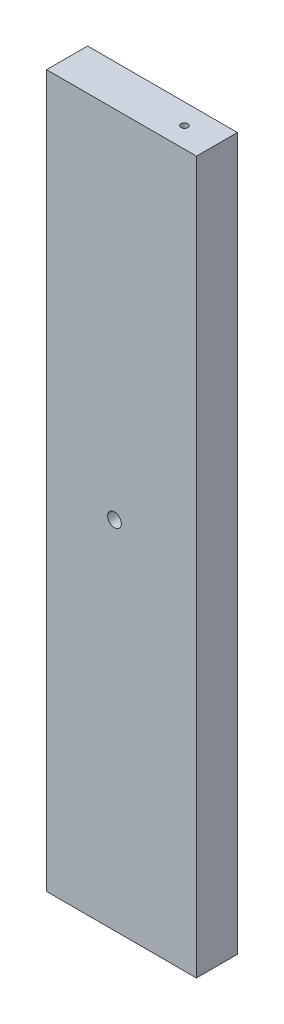
SolidWorks part; units mm, degrees
material "Beech"
ref_plane "Front Plane" through (0, 0, 0) normal (0, 0, 1) x (1, 0, 0)
ref_plane "Top Plane" through (0, 0, 0) normal (0, 1, 0) x (1, 0, 0)
ref_plane "Right Plane" through (0, 0, 0) normal (1, 0, 0) x (0, 0, -1)
sketch "Sketch1" plane through (0, 0, 0) normal (0, 0, 1) x (1, 0, 0)
  line L1 (209.353, 93.45) -> (279.0199, 93.45)
  line L2 (209.353, 93.45) -> (209.353, -237.5)
  line L3 (209.353, -237.5) -> (279.0199, -237.5)
  line L4 (279.0199, 93.45) -> (279.0199, -237.5)
  point P4 (279.0199, -237.5)
  dimension "D1" = 69.667
extrude "Boss-Extrude1" add sketch "Sketch1" along normal blind 19.05
hole_wizard "Hole1" [suppressed] positions "Sketch2" profile "Sketch3" legacy
sketch "Sketch2" [suppressed] plane through (196.653, -72.025, 386.2628) normal (-1, 0, 0) x (0, 1, 0)
  point P49 (175, 685.961)
  point P51 (175, 549.8373)
  point P53 (175, 413.7135)
  point P67 (81.55, 779.6497)
  point P73 (81.55, 652.3446)
  point P79 (62.5, 662.9534)
  point P83 (62.5, 769.041)
  point P103 (-62.5, 769.041)
  point P105 (-62.5, 662.9534)
  point P106 (-81.55, 652.3446)
  point P109 (-81.55, 779.6497)
  point P110 (-175, 413.7135)
  point P111 (-175, 549.8373)
  point P112 (-175, 685.961)
  point P115 (-82.7375, 600.3846)
  point P117 (0, 600.3846)
  point P119 (82.7375, 600.3846)
  point P129 (0, 376.7378)
  point P131 (-82.7375, 376.7378)
  point P133 (82.7375, 376.7378)
sketch "Sketch3" plane through (196.653, 102.975, -299.6982) normal (0, 1, 0) x (0, 0, 1)
  line L0 (0, 0) -> (0, 32.7039)
  line L1 (0, 32.7039) -> (1.5875, 31.75)
  line L2 (1.5875, 31.75) -> (1.5875, 4.0177)
  line L3 (1.5875, 4.0177) -> (5.08, 0)
  line L4 (5.08, 0) -> (0, 0)
  line L5 (0, -14.3089) -> (0, 102.4216) construction
  line L6 (0, 32.7039) -> (-1.5875, 31.75) construction
  line L7 (-1.5875, 4.0177) -> (-5.08, 0) construction
  dimension "Diameter" = 3.175
  dimension "Depth" = 31.75
  dimension "C-Sink Diameter" = 10.16
  dimension "C-Sink Angle" = 82
  dimension "Drill Angle" = 118
hole_wizard "Hole3" positions "Sketch6" profile "Sketch7" legacy
sketch "Sketch6" plane through (-181.0394, 112.5, 410.3892) normal (0, 1, 0) x (0.9272, 0, -0.3746)
  line L0 (48.5061, 138.7859) -> (35.9701, 0) construction
  line L5 (414.5728, 105.7206) -> (405.0235, 0) construction
  line L7 (490.0108, 170.6797) -> (621.0107, 117.7523) construction
  line L12 (503.094, 203.0616) -> (634.0938, 150.1342) construction
  line L16 (586.8736, 410.4234) -> (717.8734, 357.496) construction
  line L19 (597.4602, 127.2674) -> (610.5433, 159.6493) construction
  line L20 (610.5433, 159.6493) -> (694.3229, 367.011) construction
  line L22 (513.5613, 161.1647) -> (526.6445, 193.5466) construction
  line L23 (526.6445, 193.5466) -> (610.424, 400.9084) construction
  point P0 (46.2211, 113.4889)
  point P2 (39.3976, 37.9455)
  point P4 (412.2879, 80.4236)
  point P51 (407.3085, 25.297)
  point P56 (513.5613, 161.1647)
  point P58 (597.4602, 127.2674)
  point P61 (610.5433, 159.6493)
  point P63 (694.3229, 367.011)
  point P66 (526.6445, 193.5466)
  point P68 (610.424, 400.9084)
sketch "Sketch7" plane through (-180.6976, 112.5, 287.8494) normal (1, 0, 0) x (0, 0, 1)
  line L0 (0, 0) -> (0, 39.0539)
  line L1 (0, 39.0539) -> (1.5875, 38.1)
  line L2 (1.5875, 38.1) -> (1.5875, 4.0177)
  line L3 (1.5875, 4.0177) -> (5.08, 0)
  line L4 (5.08, 0) -> (0, 0)
  line L5 (0, -14.3089) -> (0, 102.4216) construction
  line L6 (0, 39.0539) -> (-1.5875, 38.1) construction
  line L7 (-1.5875, 4.0177) -> (-5.08, 0) construction
  dimension "Diameter" = 3.175
  dimension "Depth" = 38.1
  dimension "C-Sink Diameter" = 10.16
  dimension "C-Sink Angle" = 82
  dimension "Drill Angle" = 118
hole_wizard "1/4 (0.25) Diameter Hole1" positions "Sketch10" profile "Sketch11" hole size "1/4" standard "ANSI Inch" end condition through all
sketch "Sketch10" plane through (0, 0, 0) normal (0, 0, -1) x (-1, 0, 0)
  point P0 (-240.9199, -72.025)
  point P1 (0, 0)
  point P2 (-240.9199, -72.025)
sketch "Sketch11" plane through (240.9199, -72.025, 0) normal (1, 0, 0) x (0, 1, 0)
  line L0 (0, 0) -> (0, 19.05)
  line L1 (0, 19.05) -> (3.175, 19.05)
  line L2 (3.175, 19.05) -> (3.175, 0)
  line L5 (3.175, 0) -> (0, 0)
  line L11 (0, -6.35) -> (0, 107.95) construction
  dimension "Thru Hole Dia." = 6.35
  dimension "Thru Hole Depth" = 19.05
hole_wizard "Hole4" [suppressed] positions "Sketch12" profile "Sketch13" legacy
sketch "Sketch12" [suppressed] plane through (196.653, -72.025, 609.9096) normal (-1, 0, 0) x (0, 1, 0)
  point P49 (175, 685.961)
  point P51 (175, 549.8373)
  point P53 (175, 413.7135)
  point P67 (81.55, 779.6497)
  point P73 (81.55, 652.3446)
  point P79 (62.5, 662.9534)
  point P83 (62.5, 769.041)
  point P103 (-62.5, 769.041)
  point P105 (-62.5, 662.9534)
  point P106 (-81.55, 652.3446)
  point P109 (-81.55, 779.6497)
  point P110 (-175, 413.7135)
  point P111 (-175, 549.8373)
  point P112 (-175, 685.961)
  point P115 (-82.7375, 600.3846)
  point P117 (0, 600.3846)
  point P119 (82.7375, 600.3846)
  point P129 (0, 376.7378)
  point P131 (-82.7375, 376.7378)
  point P133 (82.7375, 376.7378)
sketch "Sketch13" plane through (196.653, 102.975, -76.0514) normal (0, 1, 0) x (0, 0, 1)
  line L0 (0, 0) -> (0, 32.7039)
  line L1 (0, 32.7039) -> (1.5875, 31.75)
  line L2 (1.5875, 31.75) -> (1.5875, 4.0177)
  line L3 (1.5875, 4.0177) -> (5.08, 0)
  line L4 (5.08, 0) -> (0, 0)
  line L5 (0, -14.3089) -> (0, 102.4216) construction
  line L6 (0, 32.7039) -> (-1.5875, 31.75) construction
  line L7 (-1.5875, 4.0177) -> (-5.08, 0) construction
  dimension "Diameter" = 3.175
  dimension "Depth" = 31.75
  dimension "C-Sink Diameter" = 10.16
  dimension "C-Sink Angle" = 82
  dimension "Drill Angle" = 118
hole_wizard "Hole5" positions "Sketch14" profile "Sketch15" legacy
sketch "Sketch14" plane through (-181.0394, 112.5, 580.9729) normal (0, 1, 0) x (0.9272, 0, -0.3746)
  line L0 (79.9741, 138.7859) -> (67.4382, 0) construction
  line L5 (446.0409, 105.7206) -> (436.4916, 0) construction
  line L7 (526.1009, 182.1196) -> (590.695, 156.0219) construction
  line L12 (512.1319, 225.4312) -> (576.726, 199.3335) construction
  line L16 (576.0337, 383.5937) -> (640.6278, 357.496) construction
  line L19 (567.1445, 165.5369) -> (580.2277, 197.9188) construction
  line L20 (580.2277, 197.9188) -> (644.1295, 356.0812) construction
  line L22 (549.6514, 172.6046) -> (562.7345, 204.9865) construction
  line L23 (562.7345, 204.9865) -> (626.6363, 363.1489) construction
  point P0 (77.6892, 113.4889)
  point P2 (70.8657, 37.9455)
  point P4 (443.7559, 80.4236)
  point P51 (438.7766, 25.297)
  point P56 (549.6514, 172.6046)
  point P58 (567.1445, 165.5369)
  point P61 (580.2277, 197.9188)
  point P63 (644.1295, 356.0812)
  point P66 (562.7345, 204.9865)
  point P68 (626.6363, 363.1489)
sketch "Sketch15" plane through (-151.521, 112.5, 446.645) normal (1, 0, 0) x (0, 0, 1)
  line L0 (0, 0) -> (0, 39.0539)
  line L1 (0, 39.0539) -> (1.5875, 38.1)
  line L2 (1.5875, 38.1) -> (1.5875, 4.0177)
  line L3 (1.5875, 4.0177) -> (5.08, 0)
  line L4 (5.08, 0) -> (0, 0)
  line L5 (0, -14.3089) -> (0, 102.4216) construction
  line L6 (0, 39.0539) -> (-1.5875, 38.1) construction
  line L7 (-1.5875, 4.0177) -> (-5.08, 0) construction
  dimension "Diameter" = 3.175
  dimension "Depth" = 38.1
  dimension "C-Sink Diameter" = 10.16
  dimension "C-Sink Angle" = 82
  dimension "Drill Angle" = 118
